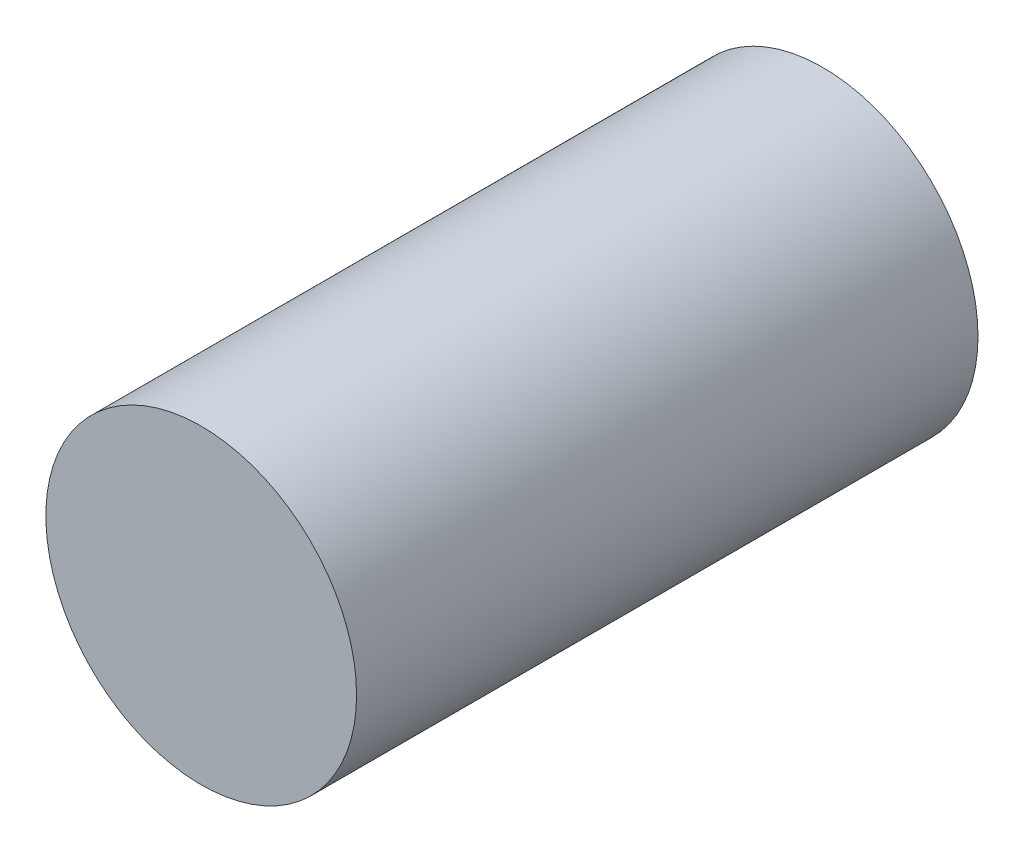
SolidWorks part; units mm, degrees
material "AISI 1045 Steel, cold drawn"
ref_plane "Front Plane" through (0, 0, 0) normal (0, 0, 1) x (1, 0, 0)
ref_plane "Top Plane" through (0, 0, 0) normal (0, 1, 0) x (1, 0, 0)
ref_plane "Right Plane" through (0, 0, 0) normal (1, 0, 0) x (0, 0, -1)
sketch "Sketch1" plane through (0, 0, 0) normal (0, 0, 1) x (1, 0, 0)
  circle A0 centre (0, 0) radius 10
  dimension "D1" = 20
extrude "Boss-Extrude1" add sketch "Sketch1" along normal mid plane 40 contours A0
